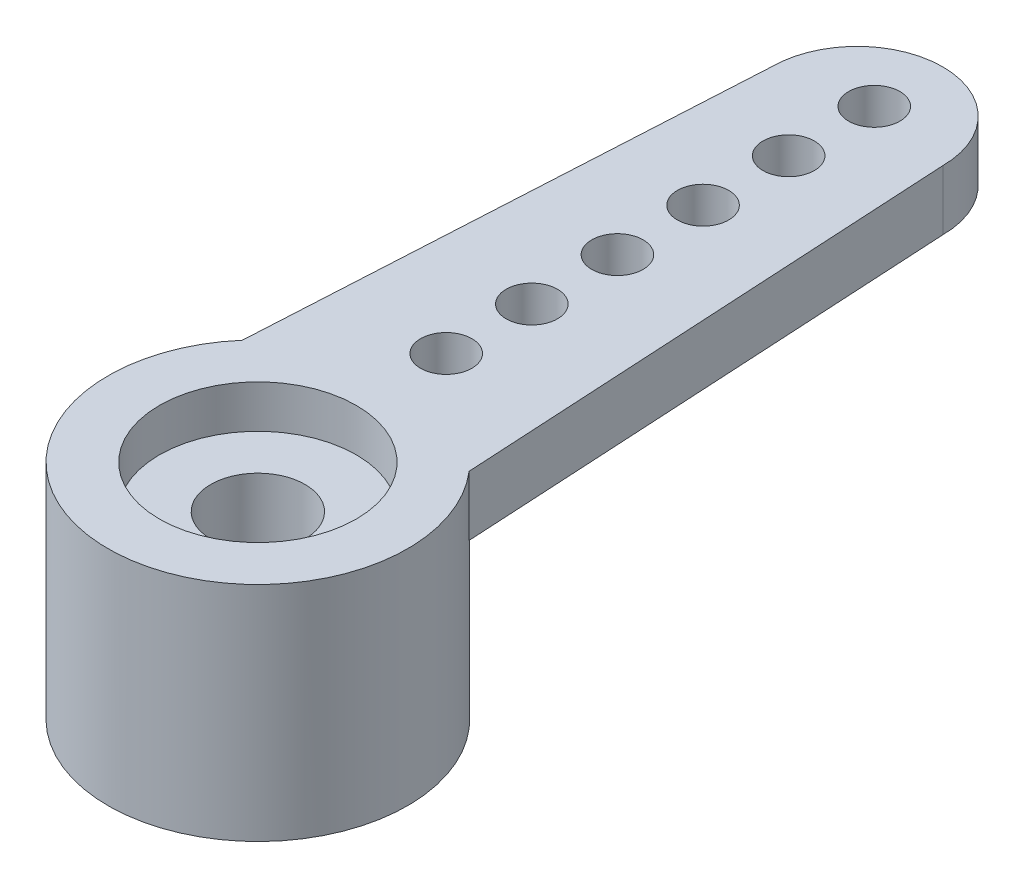
SolidWorks part; units mm, degrees
ref_plane "Front Plane" through (0, 0, 0) normal (0, 0, 1) x (1, 0, 0)
ref_plane "Top Plane" through (0, 0, 0) normal (0, 1, 0) x (1, 0, 0)
ref_plane "Right Plane" through (0, 0, 0) normal (1, 0, 0) x (0, 0, -1)
sketch "Sketch1" plane through (0, 0, 0) normal (0, 1, 0) x (1, 0, 0)
  line L0 (0, 14.4) -> (0, 0)
  line L2 (-2, 14) -> (-2.65, 2.2864)
  line L3 (2, 14) -> (2.65, 2.2864)
  arc A1 (2, 14) -> (-2, 14) centre (0, 14) ccw
  circle A2 centre (0, 14.4) radius 0.6
  circle A3 centre (0, 12.4) radius 0.6
  circle A4 centre (0, 10.4) radius 0.6
  circle A5 centre (0, 8.4) radius 0.6
  circle A6 centre (0, 6.4) radius 0.6
  circle A7 centre (0, 4.4) radius 0.6
  arc A16 (2.65, -2.2864) -> (2.65, 2.2864) centre (0, 0) ccw
  arc A17 (-2.65, 2.2864) -> (2.65, 2.2864) centre (0, 0) ccw
  dimension "D2" = 4
  dimension "D6" = 1.2
  dimension "D3" = 14
  dimension "D4" = 5.3
  dimension "D7" = 6
extrude "Boss-Extrude1" add sketch "Sketch1" against normal blind 1.4
sketch "Sketch2" plane through (0, -1.4, 0) normal (0, -1, 0) x (-1, 0, 0)
  circle A0 centre (0, 0) radius 3.5
extrude "Boss-Extrude2" add sketch "Sketch2" along normal blind 3.8
sketch "Sketch3" plane through (0, 0, 0) normal (0, 1, 0) x (1, 0, 0)
  circle A0 centre (0, 0) radius 2.3
  dimension "D1" = 4.6
extrude "Cut-Extrude1" cut sketch "Sketch3" against normal blind 1
sketch "Sketch4" plane through (0, -5.2, 0) normal (0, -1, 0) x (-1, 0, 0)
  circle A0 centre (0, 0) radius 2.5
  dimension "D1" = 5
extrude "Cut-Extrude2" cut sketch "Sketch4" against normal blind 2
sketch "Sketch5" plane through (0, -1, 0) normal (0, 1, 0) x (1, 0, 0)
  circle A0 centre (0, 0) radius 1.1022
extrude "Cut-Extrude3" cut sketch "Sketch5" against normal up to next
